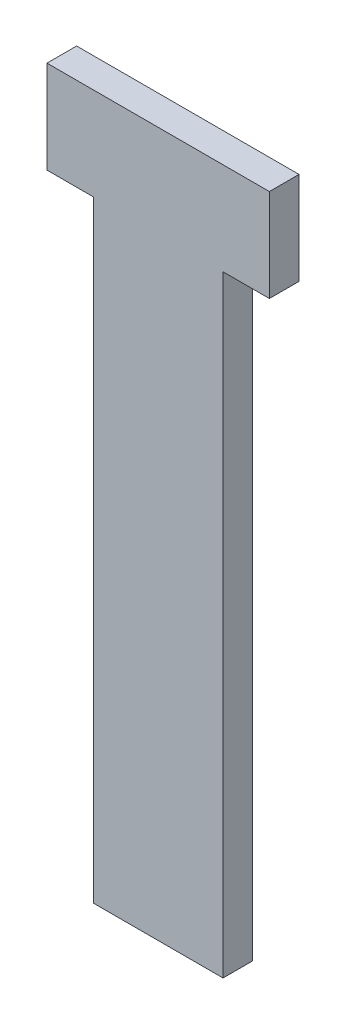
SolidWorks part; units mm, degrees
material "S235JR"
ref_plane "Piano X" through (0, 0, 0) normal (0, 0, 1) x (1, 0, 0)
ref_plane "Piano Y" through (0, 0, 0) normal (0, 1, 0) x (1, 0, 0)
ref_plane "Piano Z" through (0, 0, 0) normal (1, 0, 0) x (0, 0, -1)
sketch "Schizzo1" plane through (0, 0, 0) normal (0, 0, 1) x (1, 0, 0)
  line L0 (-3.5, 33) -> (-6, 33)
  line L1 (6, 38) -> (-6, 38)
  line L2 (3.5, 33) -> (3.5, 0)
  line L3 (3.5, 0) -> (-3.5, 0)
  line L4 (-3.5, 33) -> (-3.5, 0)
  line L5 (0, 0) -> (0, 38) construction
  line L6 (3.5, 16.5) -> (-3.5, 16.5) construction
  line L7 (-6, 33) -> (-6, 38)
  line L8 (6, 38) -> (6, 33)
  line L9 (6, 33) -> (3.5, 33)
  point P0 (0, 16.5)
  dimension "D1" = 7
  dimension "D2" = 5
  dimension "D3" = 33
  dimension "D4" = 12
extrude "Estrusione-Estrusione1" add sketch "Schizzo1" along normal blind 1.6
